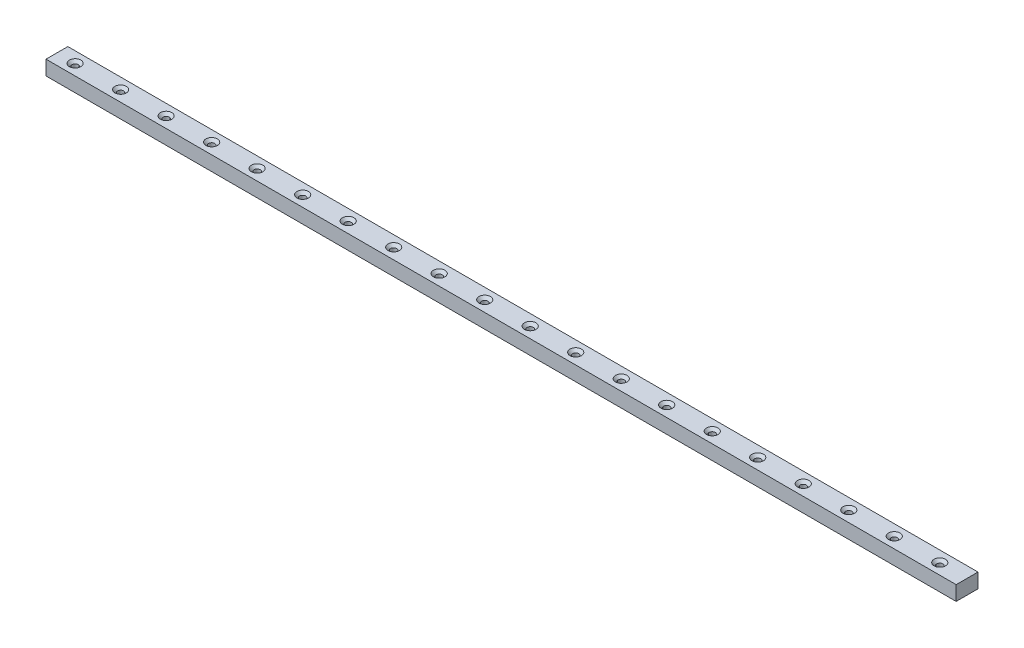
SolidWorks part; units mm, degrees
ref_plane "Front Plane" through (0, 0, 0) normal (0, 0, 1) x (1, 0, 0)
ref_plane "Top Plane" through (0, 0, 0) normal (0, 1, 0) x (1, 0, 0)
ref_plane "Right Plane" through (0, 0, 0) normal (1, 0, 0) x (0, 0, -1)
sketch "Sketch1" plane through (0, 0, 0) normal (1, 0, 0) x (0, 0, -1)
  line L1 (-6, -4) -> (6, -4)
  line L2 (-6, -4) -> (-6, 4)
  line L3 (-6, 4) -> (6, 4)
  line L4 (6, -4) -> (6, 4)
  line L5 (-6, -4) -> (6, 4) construction
  line L6 (-6, 4) -> (6, -4) construction
  point P0 (0, 0)
  dimension "D1" = 12
  dimension "D2" = 8
extrude "Boss-Extrude1" add sketch "Sketch1" along normal blind 500 contours L3 L4 L1 L2
hole_wizard "CSK for M3 Flat Head Machine Screw1" positions "Sketch4" profile "Sketch3" countersink size "M3" standard "ANSI Metric" end condition through all
sketch "Sketch4" plane through (0, 4, 0) normal (0, 1, 0) x (1, 0, 0)
  line L0 (500, 6) -> (0, 6) construction
  point P0 (10, 0)
  dimension "D1" = 10
  dimension "D2" = 6
sketch "Sketch3" plane through (10, 4, 0) normal (1, 0, 0) x (0, 0, 1)
  line L0 (0, 0) -> (0, 8)
  line L1 (0, 8) -> (1.7, 8)
  line L2 (1.7, 8) -> (1.7, 1.45)
  line L3 (1.7, 1.45) -> (3.15, 0)
  line L5 (3.15, 0) -> (0, 0)
  line L6 (-1.7, 1.45) -> (-3.15, 0) construction
  line L11 (0, -6.35) -> (0, 107.95) construction
  dimension "Thru Hole Dia." = 3.4
  dimension "Thru Hole Depth" = 8
  dimension "Near C'Sink Dia." = 6.3
  dimension "Near C'Sink Angle" = 90
pattern_linear "LPattern1" count 20 spacing 25 along (1, 0, 0) of "CSK for M3 Flat Head Machine Screw1"
